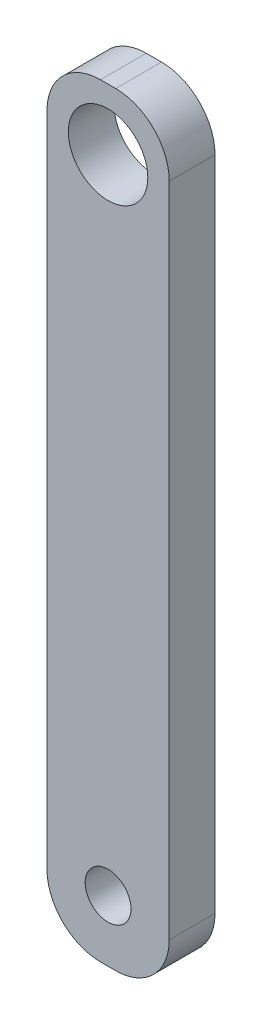
SolidWorks part; units mm, degrees
material "PE High Density"
ref_plane "Front Plane" through (0, 0, 0) normal (1, 0, 0) x (0, 1, 0)
ref_plane "Top Plane" through (0, 0, 0) normal (0, 0, 1) x (0, 1, 0)
ref_plane "Right Plane" through (0, 0, 0) normal (0, 1, 0) x (-1, 0, 0)
sketch "Sketch1" plane through (0, 0, 0) normal (0, 0, 1) x (0, 1, 0)
  line L1 (-25, 4) -> (25, 4)
  line L2 (-25, 4) -> (-25, -4)
  line L3 (-25, -4) -> (25, -4)
  line L4 (25, 4) -> (25, -4)
  line L5 (-25, 4) -> (25, -4) construction
  line L6 (-25, -4) -> (25, 4) construction
  circle A0 centre (-21, 0) radius 1.5
  circle A1 centre (21, 0) radius 2.6
  point P0 (0, 0)
  dimension "D1" = 3
  dimension "D2" = 5.2
  dimension "D3" = 8
  dimension "D4" = 50
  dimension "D5" = 4
  dimension "D6" = 4
  dimension "D7" = 4
  dimension "D8" = 4
extrude "Boss-Extrude1" add sketch "Sketch1" against normal blind 3 contours L1 L4 L3 L2
fillet "Fillet1" radius 3.5 4 edges at (4, 25, -1.5) (-4, 25, -1.5) (4, -25, -1.5) (-4, -25, -1.5)
scale "Scale1" scale about centroid uniform scaling yes scale factor 0.7
